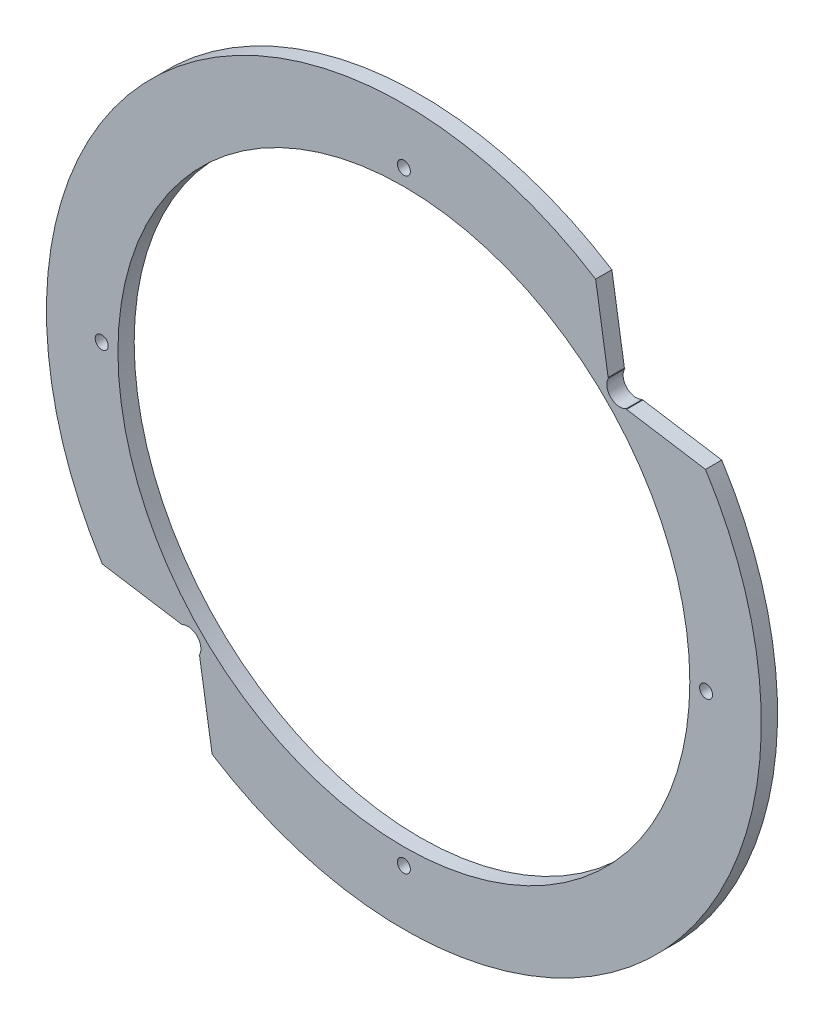
SolidWorks part; units mm, degrees
ref_plane "Front Plane" through (0, 0, 0) normal (0, 0, 1) x (1, 0, 0)
ref_plane "Top Plane" through (0, 0, 0) normal (0, 1, 0) x (1, 0, 0)
ref_plane "Right Plane" through (0, 0, 0) normal (1, 0, 0) x (0, 0, -1)
sketch "Sketch1" plane through (0, 0, 0) normal (0, 0, 1) x (1, 0, 0)
  line L0 (-78.3987, -3.3654) -> (61.3013, -3.3654) construction
  line L1 (-5.8227, 60.5836) -> (-5.8227, 59.1774)
  line L2 (-57.9401, 46.026) -> (40.8427, -52.7569) construction
  line L3 (40.8427, 46.026) -> (-57.9401, -52.7569) construction
  line L4 (-13.4427, 60.5073) -> (-13.4427, 59.1774)
  line L5 (-13.4427, 59.1774) -> (-5.8227, 59.1774)
  line L12 (2.7798, 58.212) -> (10.1401, 56.2398)
  line L13 (10.5041, 57.5981) -> (10.1401, 56.2398)
  line L14 (3.124, 59.4967) -> (2.7798, 58.212)
  line L18 (18.1997, 53.0809) -> (24.7988, 49.2709)
  line L19 (25.5019, 50.4887) -> (24.7988, 49.2709)
  line L20 (18.8647, 54.2327) -> (18.1997, 53.0809)
  line L24 (31.7661, 44.1336) -> (37.1543, 38.7454)
  line L25 (38.1486, 39.7398) -> (37.1543, 38.7454)
  line L26 (32.7065, 45.074) -> (31.7661, 44.1336)
  line L30 (42.5546, 31.9799) -> (46.3646, 25.3808)
  line L31 (47.5824, 26.0839) -> (46.3646, 25.3808)
  line L32 (43.7063, 32.6449) -> (42.5546, 31.9799)
  line L36 (49.8298, 17.4482) -> (51.802, 10.0878)
  line L37 (53.1603, 10.4518) -> (51.802, 10.0878)
  line L38 (51.1145, 17.7924) -> (49.8298, 17.4482)
  line L42 (53.0961, 1.5286) -> (53.0961, -6.0914)
  line L43 (54.5023, -6.0914) -> (53.0961, -6.0914)
  line L44 (54.426, 1.5286) -> (53.0961, 1.5286)
  line L48 (52.1307, -14.6939) -> (50.1585, -22.0543)
  line L49 (51.5168, -22.4183) -> (50.1585, -22.0543)
  line L50 (53.4154, -15.0382) -> (52.1307, -14.6939)
  line L54 (46.9996, -30.1138) -> (43.1896, -36.713)
  line L55 (44.4074, -37.4161) -> (43.1896, -36.713)
  line L56 (48.1513, -30.7788) -> (46.9996, -30.1138)
  line L60 (38.0523, -43.6803) -> (32.6641, -49.0684)
  line L61 (33.6585, -50.0628) -> (32.6641, -49.0684)
  line L62 (38.9927, -44.6207) -> (38.0523, -43.6803)
  line L66 (25.8986, -54.4687) -> (19.2995, -58.2787)
  line L67 (20.0026, -59.4965) -> (19.2995, -58.2787)
  line L68 (26.5636, -55.6205) -> (25.8986, -54.4687)
  line L72 (11.3669, -61.744) -> (4.0065, -63.7162)
  line L73 (4.3705, -65.0745) -> (4.0065, -63.7162)
  line L74 (11.7111, -63.0286) -> (11.3669, -61.744)
  line L78 (-4.5527, -65.0102) -> (-12.1727, -65.0102)
  line L79 (-12.1727, -66.4164) -> (-12.1727, -65.0102)
  line L80 (-4.5527, -66.3402) -> (-4.5527, -65.0102)
  line L84 (-20.7752, -64.0449) -> (-28.1356, -62.0727)
  line L85 (-28.4996, -63.431) -> (-28.1356, -62.0727)
  line L86 (-21.1195, -65.3295) -> (-20.7752, -64.0449)
  line L90 (-36.1951, -58.9137) -> (-42.7943, -55.1037)
  line L91 (-43.4974, -56.3215) -> (-42.7943, -55.1037)
  line L92 (-36.8601, -60.0655) -> (-36.1951, -58.9137)
  line L96 (-49.7616, -49.9665) -> (-55.1497, -44.5783)
  line L97 (-56.1441, -45.5726) -> (-55.1497, -44.5783)
  line L98 (-50.702, -50.9069) -> (-49.7616, -49.9665)
  line L102 (-60.55, -37.8128) -> (-64.36, -31.2137)
  line L103 (-65.5778, -31.9168) -> (-64.36, -31.2137)
  line L104 (-61.7018, -38.4778) -> (-60.55, -37.8128)
  line L109 (-71.1558, -16.2846) -> (-69.7975, -15.9207)
  line L110 (-69.1099, -23.6252) -> (-67.8253, -23.281)
  line L114 (-71.0915, -7.3614) -> (-71.0915, 0.2586)
  line L115 (-72.4977, 0.2586) -> (-71.0915, 0.2586)
  line L116 (-72.4215, -7.3614) -> (-71.0915, -7.3614)
  line L120 (-70.1262, 8.8611) -> (-68.154, 16.2214)
  line L121 (-69.5123, 16.5854) -> (-68.154, 16.2214)
  line L122 (-71.4108, 9.2053) -> (-70.1262, 8.8611)
  line L126 (-64.995, 24.281) -> (-61.185, 30.8801)
  line L127 (-62.4028, 31.5832) -> (-61.185, 30.8801)
  line L128 (-66.1468, 24.946) -> (-64.995, 24.281)
  line L132 (-56.0478, 37.8474) -> (-50.6596, 43.2356)
  line L133 (-51.6539, 44.2299) -> (-50.6596, 43.2356)
  line L134 (-56.9882, 38.7878) -> (-56.0478, 37.8474)
  line L138 (-43.8941, 48.6359) -> (-37.295, 52.4459)
  line L139 (-37.9981, 53.6637) -> (-37.295, 52.4459)
  line L140 (-44.5591, 49.7877) -> (-43.8941, 48.6359)
  line L144 (-29.3623, 55.9111) -> (-22.002, 57.8833)
  line L145 (-22.3659, 59.2416) -> (-22.002, 57.8833)
  line L146 (-29.7065, 57.1958) -> (-29.3623, 55.9111)
  line L147 (-8.9977, -2.9164) -> (-5.8227, 59.1774) construction
  line L148 (-8.9977, -2.9164) -> (10.1401, 56.2398) construction
  line L170 (-67.8253, -23.281) -> (-69.7975, -15.9207) [skipped]
  circle A0 centre (-8.5487, -3.3654) radius 55.88
  circle A1 centre (-8.5487, -3.3654) radius 69.85
  dimension "D1" = 111.76
  dimension "D2" = 139.7
  dimension "D4" = 7.62
  dimension "D5" = 24
  dimension "D6" = 15
extrude "Boss-Extrude1" add sketch "Sketch1" along normal blind 3.175
sketch "Sketch4" plane through (0, 0, 0) normal (0, 0, -1) x (-1, 0, 0)
  line L0 (8.5487, 52.5146) -> (8.5487, -59.2454) construction
  line L1 (-47.3313, -3.3654) -> (64.4287, -3.3654) construction
  line L2 (8.5487, -3.3654) -> (81.6471, -76.4638) construction
  line L3 (8.5487, -3.3654) -> (-56.7065, 61.8898) construction
  line L5 (-58.9165, 50.8304) -> (-50.3971, 34.1101)
  line L6 (-50.3971, 34.1101) -> (-31.8624, 37.0457)
  line L7 (-31.8624, 37.0457) -> (-28.9268, 55.5803)
  line L8 (-28.9268, 55.5803) -> (-45.6472, 64.0998)
  line L9 (-45.6472, 64.0998) -> (-58.9165, 50.8304)
  line L10 (67.4945, -40.841) -> (48.9599, -43.7766)
  line L11 (48.9599, -43.7766) -> (46.0243, -62.3112)
  line L12 (46.0243, -62.3112) -> (62.7446, -70.8307)
  line L13 (62.7446, -70.8307) -> (76.0139, -57.5613)
  line L14 (76.0139, -57.5613) -> (67.4945, -40.841)
  circle A0 centre (8.5487, -3.3654) radius 55.88 construction
  circle A1 centre (8.5487, -3.3654) radius 59.055
  circle A2 centre (8.5487, 55.6896) radius 1.27
  circle A3 centre (8.5487, -62.4204) radius 1.27
  circle A4 centre (-50.5063, -3.3654) radius 1.27
  circle A5 centre (67.6037, -3.3654) radius 1.27
  circle A6 centre (8.5487, -3.3654) radius 62.23
  circle A7 centre (-33.6585, 38.8418) radius 2.54
  circle A8 centre (50.7559, -45.5726) radius 2.54
  circle A9 centre (-43.15, 48.3333) radius 12.9144 construction
  circle A10 centre (8.5487, -3.3654) radius 69.85 construction
  circle A11 centre (60.2474, -55.0642) radius 12.9144 construction
  circle M19 centre (8.5487, -3.3654) radius 69.85
  dimension "D1" = 118.11
  dimension "D2" = 2.54
  dimension "D3" = 2.54
  dimension "D4" = 2.54
  dimension "D5" = 2.54
  dimension "D8" = 124.46
  dimension "D9" = 5.08
  dimension "D10" = 5.08
  dimension "D6" = 45
  dimension "D7" = 45
extrude "Cut-Extrude2" cut sketch "Sketch4" against normal through all contours A1 A2 | A1 A2 | A1 A4 | A1 A4 | A1 A3 | A1 A3 | A1 A5 | A1 A5 | A1 A7 | A1 A7 | A1 A8 | A1 A8 | A6 L11 L10 M19 | A8 A6 L10 A1 | A8 A1 L11 A6 | A6 L7 L6 M19 | A7 A1 L7 A6 | A7 A6 L6 A1 | L6 A7 | L7 A7 | L10 A8 | L11 A8
